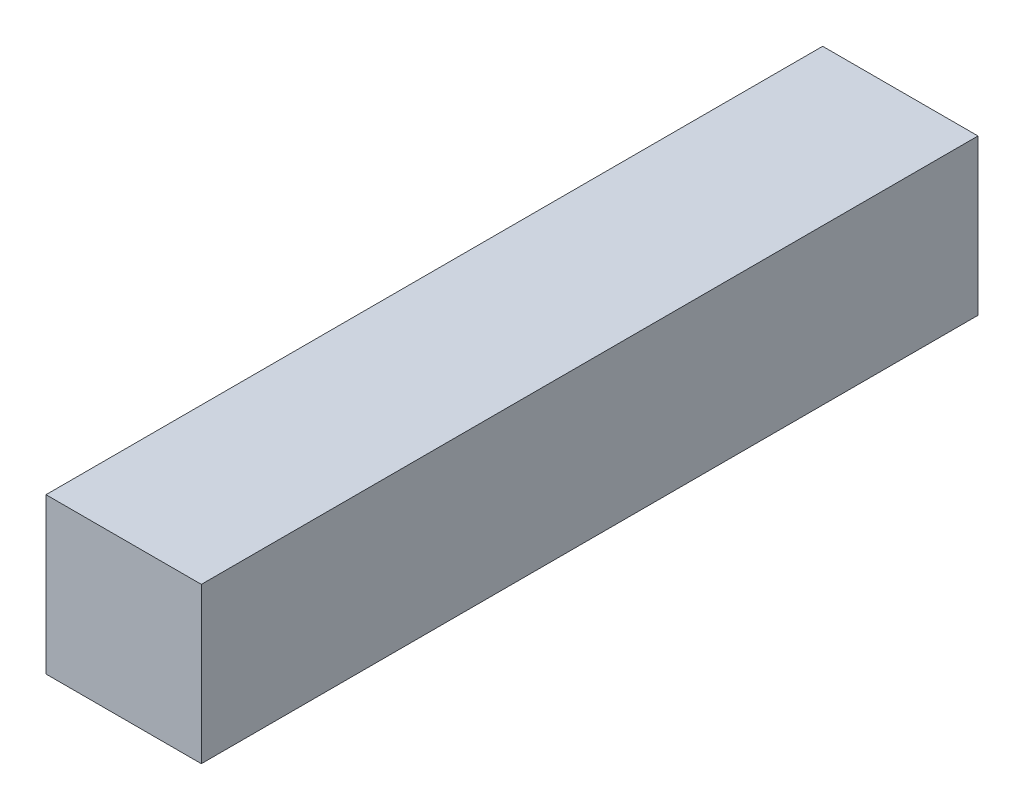
SolidWorks part; units mm, degrees
ref_plane "Front Plane" through (0, 0, 0) normal (0, 0, 1) x (1, 0, 0)
ref_plane "Top Plane" through (0, 0, 0) normal (0, 1, 0) x (1, 0, 0)
ref_plane "Right Plane" through (0, 0, 0) normal (1, 0, 0) x (0, 0, -1)
sketch "Sketch2" plane through (0, 0, 0) normal (0, 1, 0) x (1, 0, 0)
  line L1 (-2, -10) -> (2, -10)
  line L2 (-2, -10) -> (-2, 10)
  line L3 (-2, 10) -> (2, 10)
  line L4 (2, -10) -> (2, 10)
  line L5 (-2, -10) -> (2, 10) construction
  line L6 (-2, 10) -> (2, -10) construction
  point P0 (0, 0)
  dimension "D1" = 20
  dimension "D2" = 4
extrude "Boss-Extrude1" add sketch "Sketch2" along normal blind 4
